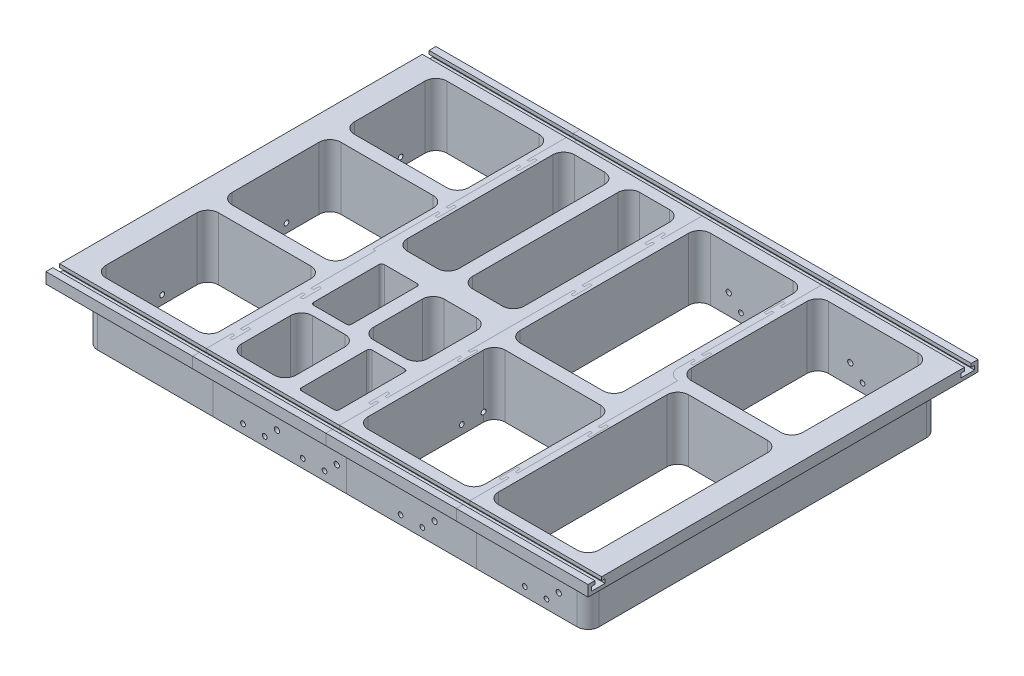
SolidWorks part; units mm, degrees
ref_plane "Front Plane" through (0, 0, 0) normal (0, 0, 1) x (1, 0, 0)
ref_plane "Top Plane" through (0, 0, 0) normal (0, 1, 0) x (1, 0, 0)
ref_plane "Right Plane" through (0, 0, 0) normal (1, 0, 0) x (0, 0, -1)
sketch "Sketch1" plane through (0, 0, 0) normal (0, 1, 0) x (1, 0, 0)
  line L1 (199.5, -143.5) -> (-199.5, -143.5)
  line L2 (199.5, -143.5) -> (199.5, 143.5)
  line L3 (199.5, 143.5) -> (-199.5, 143.5)
  line L4 (-199.5, -143.5) -> (-199.5, 143.5)
  line L5 (199.5, -143.5) -> (-199.5, 143.5) construction
  line L6 (199.5, 143.5) -> (-199.5, -143.5) construction
  point P0 (0, 0)
  dimension "D1" = 399
  dimension "D2" = 287
extrude "Boss-Extrude1" add sketch "Sketch1" along normal blind 53
sketch "Sketch3" plane through (0, 0, 0) normal (0, -1, 0) x (-1, 0, 0)
  line L23 (184.5, -128.5) -> (184.5, 128.5)
  line L24 (184.5, 128.5) -> (-184.5, 128.5)
  line L25 (-184.5, 128.5) -> (-184.5, -128.5)
  line L26 (-184.5, -128.5) -> (184.5, -128.5)
  line L27 (184.5, -128.5) -> (184.5, 128.5)
  line L28 (184.5, 128.5) -> (-184.5, 128.5)
  line L29 (-184.5, 128.5) -> (-184.5, -128.5)
  line L30 (-184.5, -128.5) -> (184.5, -128.5)
  dimension "D1" = 15
extrude "Cut-Extrude2" cut sketch "Sketch3" against normal blind 45 flip side to cut
sketch "Sketch2" plane through (0, 53, 0) normal (0, 1, 0) x (1, 0, 0)
  line L1 (-173.5, -125.5) -> (-105.5, -125.5)
  line L2 (-181.5, -117.5) -> (-181.5, -50.5)
  line L3 (-173.5, -42.5) -> (-105.5, -42.5)
  line L4 (-97.5, -117.5) -> (-97.5, -50.5)
  line L5 (-173.5, -32.5) -> (-105.5, -32.5)
  line L6 (-181.5, -24.5) -> (-181.5, 39.5)
  line L7 (-173.5, 47.5) -> (-105.5, 47.5)
  line L8 (-181.5, 125.5) -> (-181.5, -125.5)
  line L9 (-181.5, -125.5) -> (181.5, -125.5)
  line L10 (181.5, -125.5) -> (181.5, 125.5)
  line L11 (181.5, 125.5) -> (-181.5, 125.5)
  line L12 (-181.5, 125.5) -> (-181.5, -125.5) construction
  line L13 (-181.5, -125.5) -> (181.5, -125.5) construction
  line L14 (181.5, -125.5) -> (181.5, 125.5) construction
  line L15 (181.5, 125.5) -> (-181.5, 125.5) construction
  line L16 (-97.5, -24.5) -> (-97.5, 39.5)
  line L17 (-173.5, 125.5) -> (-105.5, 125.5)
  line L18 (-181.5, 117.5) -> (-181.5, 65.5)
  line L19 (-173.5, 57.5) -> (-105.5, 57.5)
  line L20 (-97.5, 117.5) -> (-97.5, 65.5)
  line L21 (173.5, -125.5) -> (115.5, -125.5)
  line L22 (181.5, -117.5) -> (181.5, 6.5)
  line L23 (173.5, 14.5) -> (115.5, 14.5)
  line L24 (107.5, -117.5) -> (107.5, 6.5)
  line L25 (173.5, 125.5) -> (107.5, 125.5)
  line L26 (181.5, 117.5) -> (181.5, 32.5)
  line L27 (173.5, 24.5) -> (107.5, 24.5)
  line L28 (99.5, 117.5) -> (99.5, 32.5)
  line L29 (81.5, 125.5) -> (20.5, 125.5)
  line L30 (89.5, 117.5) -> (89.5, -6.5)
  line L31 (81.5, -14.5) -> (20.5, -14.5)
  line L32 (12.5, 117.5) -> (12.5, -6.5)
  line L33 (-9.5, 125.5) -> (-31.5, 125.5)
  line L34 (-1.5, 117.5) -> (-1.5, 10.5)
  line L35 (-9.5, 2.5) -> (-31.5, 2.5)
  line L36 (-39.5, 117.5) -> (-39.5, 10.5)
  line L37 (-57.5, 125.5) -> (-79.5, 125.5)
  line L38 (-49.5, 117.5) -> (-49.5, 10.5)
  line L39 (-57.5, 2.5) -> (-79.5, 2.5)
  line L40 (-87.5, 117.5) -> (-87.5, 10.5)
  line L41 (-79.5, -14.5) -> (-55.5, -14.5)
  line L42 (-81.5, -16.5) -> (-81.5, -64.5)
  line L43 (-79.5, -66.5) -> (-55.5, -66.5)
  line L44 (-53.5, -16.5) -> (-53.5, -64.5)
  line L45 (-73.5, -125.5) -> (-49.5, -125.5)
  line L46 (-81.5, -117.5) -> (-81.5, -81.5)
  line L47 (-73.5, -73.5) -> (-49.5, -73.5)
  line L48 (-41.5, -117.5) -> (-41.5, -81.5)
  line L49 (-35.5, -14.5) -> (-11.5, -14.5)
  line L50 (-43.5, -22.5) -> (-43.5, -58.5)
  line L51 (-35.5, -66.5) -> (-11.5, -66.5)
  line L52 (-3.5, -22.5) -> (-3.5, -58.5)
  line L53 (-29.5, -73.5) -> (-5.5, -73.5)
  line L54 (-31.5, -75.5) -> (-31.5, -123.5)
  line L55 (-29.5, -125.5) -> (-5.5, -125.5)
  line L56 (-3.5, -75.5) -> (-3.5, -123.5)
  line L57 (89.5, -125.5) -> (19.5, -125.5)
  line L58 (97.5, -117.5) -> (97.5, -32.5)
  line L59 (89.5, -24.5) -> (19.5, -24.5)
  line L60 (11.5, -117.5) -> (11.5, -32.5)
  arc A0 (-79.5, 125.5) -> (-87.5, 117.5) centre (-79.5, 117.5) ccw
  arc A1 (-79.5, 2.5) -> (-87.5, 10.5) centre (-79.5, 10.5) cw
  arc A2 (-49.5, 10.5) -> (-57.5, 2.5) centre (-57.5, 10.5) cw
  arc A3 (-57.5, 125.5) -> (-49.5, 117.5) centre (-57.5, 117.5) cw
  arc A4 (-31.5, 125.5) -> (-39.5, 117.5) centre (-31.5, 117.5) ccw
  arc A5 (-31.5, 2.5) -> (-39.5, 10.5) centre (-31.5, 10.5) cw
  arc A6 (-1.5, 10.5) -> (-9.5, 2.5) centre (-9.5, 10.5) cw
  arc A7 (-9.5, 125.5) -> (-1.5, 117.5) centre (-9.5, 117.5) cw
  arc A8 (20.5, 125.5) -> (12.5, 117.5) centre (20.5, 117.5) ccw
  arc A9 (20.5, -14.5) -> (12.5, -6.5) centre (20.5, -6.5) cw
  arc A10 (89.5, -6.5) -> (81.5, -14.5) centre (81.5, -6.5) cw
  arc A11 (81.5, 125.5) -> (89.5, 117.5) centre (81.5, 117.5) cw
  arc A12 (107.5, 125.5) -> (99.5, 117.5) centre (107.5, 117.5) ccw
  arc A13 (173.5, 125.5) -> (181.5, 117.5) centre (173.5, 117.5) cw
  arc A14 (181.5, 32.5) -> (173.5, 24.5) centre (173.5, 32.5) cw
  arc A15 (107.5, 24.5) -> (99.5, 32.5) centre (107.5, 32.5) cw
  arc A16 (115.5, 14.5) -> (107.5, 6.5) centre (115.5, 6.5) ccw
  arc A17 (181.5, 6.5) -> (173.5, 14.5) centre (173.5, 6.5) ccw
  arc A18 (173.5, -125.5) -> (181.5, -117.5) centre (173.5, -117.5) ccw
  arc A19 (115.5, -125.5) -> (107.5, -117.5) centre (115.5, -117.5) cw
  arc A20 (89.5, -125.5) -> (97.5, -117.5) centre (89.5, -117.5) ccw
  arc A21 (97.5, -32.5) -> (89.5, -24.5) centre (89.5, -32.5) ccw
  arc A22 (19.5, -24.5) -> (11.5, -32.5) centre (19.5, -32.5) ccw
  arc A23 (19.5, -125.5) -> (11.5, -117.5) centre (19.5, -117.5) cw
  arc A28 (-43.5, -58.5) -> (-35.5, -66.5) centre (-35.5, -58.5) ccw
  arc A29 (-11.5, -66.5) -> (-3.5, -58.5) centre (-11.5, -58.5) ccw
  arc A30 (-11.5, -14.5) -> (-3.5, -22.5) centre (-11.5, -22.5) cw
  arc A31 (-35.5, -14.5) -> (-43.5, -22.5) centre (-35.5, -22.5) ccw
  arc A36 (-49.5, -73.5) -> (-41.5, -81.5) centre (-49.5, -81.5) cw
  arc A37 (-49.5, -125.5) -> (-41.5, -117.5) centre (-49.5, -117.5) ccw
  arc A38 (-73.5, -125.5) -> (-81.5, -117.5) centre (-73.5, -117.5) cw
  arc A39 (-81.5, -81.5) -> (-73.5, -73.5) centre (-73.5, -81.5) cw
  arc A40 (-105.5, -42.5) -> (-97.5, -50.5) centre (-105.5, -50.5) cw
  arc A41 (-105.5, -125.5) -> (-97.5, -117.5) centre (-105.5, -117.5) ccw
  arc A42 (-173.5, -125.5) -> (-181.5, -117.5) centre (-173.5, -117.5) cw
  arc A43 (-181.5, -50.5) -> (-173.5, -42.5) centre (-173.5, -50.5) cw
  arc A44 (-105.5, 47.5) -> (-97.5, 39.5) centre (-105.5, 39.5) cw
  arc A45 (-105.5, -32.5) -> (-97.5, -24.5) centre (-105.5, -24.5) ccw
  arc A46 (-173.5, -32.5) -> (-181.5, -24.5) centre (-173.5, -24.5) cw
  arc A47 (-181.5, 39.5) -> (-173.5, 47.5) centre (-173.5, 39.5) cw
  arc A48 (-105.5, 125.5) -> (-97.5, 117.5) centre (-105.5, 117.5) cw
  arc A49 (-105.5, 57.5) -> (-97.5, 65.5) centre (-105.5, 65.5) ccw
  arc A50 (-181.5, 65.5) -> (-173.5, 57.5) centre (-173.5, 65.5) ccw
  arc A51 (-173.5, 125.5) -> (-181.5, 117.5) centre (-173.5, 117.5) ccw
  arc A52 (-81.5, -16.5) -> (-79.5, -14.5) centre (-79.5, -16.5) cw
  arc A53 (-79.5, -66.5) -> (-81.5, -64.5) centre (-79.5, -64.5) cw
  arc A54 (-53.5, -64.5) -> (-55.5, -66.5) centre (-55.5, -64.5) cw
  arc A55 (-55.5, -14.5) -> (-53.5, -16.5) centre (-55.5, -16.5) cw
  arc A56 (-3.5, -75.5) -> (-5.5, -73.5) centre (-5.5, -75.5) ccw
  arc A57 (-5.5, -125.5) -> (-3.5, -123.5) centre (-5.5, -123.5) ccw
  arc A58 (-31.5, -123.5) -> (-29.5, -125.5) centre (-29.5, -123.5) ccw
  arc A59 (-31.5, -75.5) -> (-29.5, -73.5) centre (-29.5, -75.5) cw
  point P54 (-87.5, 125.5)
  point P57 (-87.5, 2.5)
  point P62 (-49.5, 125.5)
  point P65 (-39.5, 125.5)
  point P72 (-1.5, 125.5)
  point P75 (12.5, 125.5)
  point P82 (89.5, 125.5)
  point P85 (99.5, 125.5)
  point P91 (181.5, 24.5)
  point P103 (107.5, -125.5)
  point P106 (97.5, -125.5)
  point P109 (97.5, -24.5)
  point P114 (11.5, -125.5)
  point P119 (-3.5, -125.5)
  point P122 (-31.5, -125.5)
  point P127 (-43.5, -66.5)
  point P130 (-3.5, -66.5)
  point P139 (-81.5, -14.5)
  point P142 (-81.5, -66.5)
  point P149 (-41.5, -125.5)
  point P152 (-81.5, -125.5)
  point P155 (-81.5, -73.5)
  point P171 (-181.5, -32.5)
  point P174 (-181.5, 47.5)
  point P177 (-97.5, 125.5)
  point P182 (-181.5, 57.5)
  point P188 (-81.5, -14.5)
  point P191 (-81.5, -66.5)
  point P200 (-3.5, -125.5)
  point P203 (-31.5, -125.5)
  dimension "D31" = 8
  dimension "D32" = 8
  dimension "D33" = 8
  dimension "D34" = 2
  dimension "D35" = 2
  dimension "D2" = 74
  dimension "D3" = 82
  dimension "D4" = 101
  dimension "D5" = 10
  dimension "D6" = 86
  dimension "D7" = 10
  dimension "D8" = 15
  dimension "D9" = 28
  dimension "D10" = 40
  dimension "D11" = 52
  dimension "D12" = 52
  dimension "D13" = 77
  dimension "D14" = 38
  dimension "D15" = 38
  dimension "D16" = 84
  dimension "D17" = 68
  dimension "D18" = 80
  dimension "D19" = 10
  dimension "D20" = 10
  dimension "D21" = 7
  dimension "D22" = 10
  dimension "D23" = 101
  dimension "D24" = 10
  dimension "D25" = 10
  dimension "D26" = 123
  dimension "D27" = 10
  dimension "D28" = 10
  dimension "D29" = 40
  dimension "D30" = 10
  dimension "D1" = 18
extrude "Mini bin cuts" cut sketch "Sketch2" against normal blind 46
fillet "Fillet1" radius 8 4 edges at (-184.5, 22.5, -128.5) (184.5, 22.5, -128.5) (184.5, 22.5, 128.5) (-184.5, 22.5, 128.5)
sketch "Sketch6" plane through (-184.5, 0, 0) normal (-1, 0, 0) x (0, 0, 1)
  line L0 (128.5, 45) -> (128.5, 0) construction
  line L1 (-128.5, 0) -> (128.5, 0)
  line L2 (-128.5, 0) -> (-128.5, 7)
  line L3 (-128.5, 7) -> (128.5, 7)
  line L4 (128.5, 0) -> (128.5, 7)
  dimension "D1" = 7
extrude "Cut-Extrude5" cut sketch "Sketch6" against normal through all
sketch "Sketch7" plane through (-184.5, 0, 0) normal (-1, 0, 0) x (0, 0, 1)
  line L0 (-120.5, 13.5) -> (120.5, 13.5) construction
  line L1 (-120.5, 45) -> (-120.5, 7) construction
  line L2 (120.5, 7) -> (120.5, 45) construction
  line L3 (120.5, 7) -> (-120.5, 7) construction
  line L4 (-91.5, 13.5) -> (-91.5, 45) construction
  line L5 (120.5, 45) -> (-120.5, 45) construction
  line L6 (-7.5, 13.5) -> (-7.5, 45) construction
  line L7 (84, 13.5) -> (84, 45) construction
  circle A0 centre (-99.5, 13.5) radius 1.75
  circle A1 centre (-83.5, 13.5) radius 1.75
  circle A2 centre (-15.5, 13.5) radius 1.75
  circle A3 centre (76, 13.5) radius 1.75
  circle A4 centre (0.5, 13.5) radius 1.75
  circle A5 centre (92, 13.5) radius 1.75
  circle A6 centre (-74.5, 21.963) radius 1.95
  circle A7 centre (101, 21.963) radius 1.95
  circle A8 centre (9.5, 21.963) radius 1.95
  dimension "D2" = 36.5
  dimension "D5" = 3.5
  dimension "D7" = 3.5
  dimension "D9" = 3.5
  dimension "D11" = 3.9
  dimension "D12" = 3.9
  dimension "D13" = 3.9
  dimension "D1" = 6.5
  dimension "D3" = 29
  dimension "D4" = 113
  dimension "D6" = 8
  dimension "D8" = 8
  dimension "D10" = 8
  dimension "D14" = 17
  dimension "D15" = 17
  dimension "D16" = 17
  dimension "D17" = 8.463
  dimension "D18" = 8.463
  dimension "D19" = 8.463
extrude "Holes Lids 1,2,3" cut sketch "Sketch7" against normal up to surface (3 mm away) up to face at (-181.5, 30, 84)
sketch "Sketch8" plane through (0, 0, 128.5) normal (0, 0, 1) x (1, 0, 0)
  line L0 (-176.5, 13.5) -> (176.5, 13.5) construction
  line L1 (-176.5, 45) -> (-176.5, 7) construction
  line L2 (176.5, 7) -> (176.5, 45) construction
  line L5 (-61.5, 45) -> (-61.5, 7) construction
  line L6 (176.5, 45) -> (-176.5, 45) construction
  line L7 (176.5, 7) -> (-176.5, 7) construction
  line L8 (-17.5, 45) -> (-17.5, 7) construction
  line L11 (145.896, 45) -> (145.896, 7) construction
  line L12 (54.5, 45) -> (54.5, 7) construction
  circle A0 centre (-69.5, 13.5) radius 1.75
  circle A1 centre (-25.5, 13.5) radius 1.75
  circle A2 centre (46.5, 13.5) radius 1.75
  circle A3 centre (137.896, 13.5) radius 1.75
  circle A4 centre (153.896, 13.5) radius 1.75
  circle A5 centre (62.5, 13.5) radius 1.75
  circle A6 centre (-9.5, 13.5) radius 1.75
  circle A7 centre (-53.5, 13.5) radius 1.75
  circle A8 centre (-44.5, 21.96) radius 1.95
  circle A9 centre (-0.5, 21.96) radius 1.95
  circle A10 centre (71.5, 21.96) radius 1.95
  circle A11 centre (162.896, 21.96) radius 1.95
  dimension "D5" = 3.5
  dimension "D6" = 3.5
  dimension "D7" = 3.5
  dimension "D8" = 3.5
  dimension "D14" = 3.9
  dimension "D16" = 8.46
  dimension "D17" = 17
  dimension "D18" = 8.46
  dimension "D19" = 17
  dimension "D20" = 8.46
  dimension "D22" = 8.46
  dimension "D1" = 115
  dimension "D2" = 159
  dimension "D3" = 6.5
  dimension "D4" = 122
  dimension "D9" = 8
  dimension "D10" = 8
  dimension "D11" = 8
  dimension "D12" = 8
  dimension "D13" = 30.604
  dimension "D15" = 17
  dimension "D21" = 17
extrude "Holes Lids 8,9,12,13" cut sketch "Sketch8" against normal up to surface (3 mm away) up to face at (54.5, 30, 125.5)
sketch "Sketch9" plane through (0, 0, -128.5) normal (0, 0, -1) x (-1, 0, 0)
  line L0 (-176.5, 13.5) -> (176.5, 13.5) construction
  line L1 (-176.5, 45) -> (-176.5, 7) construction
  line L2 (176.5, 7) -> (176.5, 45) construction
  line L3 (-140.5, 45) -> (-140.5, 7) construction
  line L4 (176.5, 45) -> (-176.5, 45) construction
  line L5 (-176.5, 7) -> (176.5, 7) construction
  line L7 (20.5, 45) -> (20.5, 7) construction
  line L8 (199.5, 45) -> (-199.5, 45) construction
  line L9 (68.5, 45) -> (68.5, 7) construction
  line L10 (-51, 45) -> (-51, 7) construction
  circle A0 centre (-148.5, 13.5) radius 1.75
  circle A1 centre (-59, 13.5) radius 1.75
  circle A2 centre (12.5, 13.5) radius 1.75
  circle A3 centre (60.5, 13.5) radius 1.75
  circle A4 centre (-132.5, 13.5) radius 1.75
  circle A5 centre (-43, 13.5) radius 1.75
  circle A6 centre (28.5, 13.5) radius 1.75
  circle A7 centre (76.5, 13.5) radius 1.75
  circle A8 centre (-123.5, 21.96) radius 1.95
  circle A9 centre (-34, 21.96) radius 1.95
  circle A10 centre (37.5, 21.96) radius 1.95
  circle A11 centre (85.5, 21.96) radius 1.95
  dimension "D6" = 3.5
  dimension "D10" = 8
  dimension "D11" = 3.5
  dimension "D12" = 3.5
  dimension "D13" = 3.5
  dimension "D14" = 3.9
  dimension "D15" = 3.9
  dimension "D16" = 3.9
  dimension "D17" = 17
  dimension "D19" = 17
  dimension "D20" = 8.46
  dimension "D21" = 8.46
  dimension "D22" = 8.46
  dimension "D23" = 8.46
  dimension "D24" = 3.9
  dimension "D25" = 17
  dimension "D1" = 6.5
  dimension "D2" = 36
  dimension "D3" = 125.5
  dimension "D4" = 197
  dimension "D5" = 245
  dimension "D7" = 8
  dimension "D8" = 8
  dimension "D9" = 8
  dimension "D18" = 17
extrude "Holes Lids 4,5,10,11" cut sketch "Sketch9" against normal up to surface (3 mm away) up to face at (51, 30, -125.5)
sketch "Sketch11" plane through (-3.5, 0, 0) normal (-1, 0, 0) x (0, 0, 1)
  line L0 (22.5, 13.5) -> (58.5, 13.5) construction
  line L1 (22.5, 7) -> (22.5, 53) construction
  line L2 (58.5, 7) -> (58.5, 53) construction
  line L3 (40.5, 7) -> (40.5, 53) construction
  line L4 (58.5, 7) -> (22.5, 7) construction
  line L5 (22.5, 53) -> (58.5, 53) construction
  circle A0 centre (32.5, 13.5) radius 1.75
  circle A1 centre (48.5, 13.5) radius 1.75
  dimension "D2" = 3.5
  dimension "D1" = 6.5
  dimension "D3" = 8
extrude "Hole Lid 7" cut sketch "Sketch11" against normal up to next
sketch "Sketch12" plane through (-81.5, 0, 0) normal (1, 0, 0) x (0, 0, -1)
  line L0 (-64.5, 13.5) -> (-16.5, 13.5) construction
  line L1 (-64.5, 7) -> (-64.5, 53) construction
  line L2 (-16.5, 7) -> (-16.5, 53) construction
  line L3 (-40.5, 7) -> (-40.5, 53) construction
  line L5 (-16.5, 7) -> (-64.5, 7) construction
  line L6 (-16.5, 53) -> (-64.5, 53) construction
  circle A0 centre (-48.5, 13.5) radius 1.75
  circle A1 centre (-32.5, 13.5) radius 1.75
  dimension "D2" = 3.5
  dimension "D1" = 6.5
  dimension "D3" = 8
extrude "Hole Lid 6" cut sketch "Sketch12" against normal blind 15
sketch "Split Lines" plane through (0, 53, 0) normal (0, 1, 0) x (1, 0, 0)
  line L1 (-97.5, 117.5) -> (-97.5, 65.5) construction
  line L3 (-79.5, -14.5) -> (-55.5, -14.5) construction
  line L4 (173.5, 14.5) -> (115.5, 14.5) construction
  line L5 (-93.5, 143.5) -> (-93.5, 104.5)
  line L6 (199.5, 143.5) -> (-199.5, 143.5) construction
  line L7 (-199.5, -143.5) -> (199.5, -143.5) construction
  line L8 (-90.25, -114.5) -> (-91.5, -114.5)
  line L9 (-89.5, -117.75) -> (-89.5, -115.25)
  line L10 (-88.25, -118.5) -> (-88.75, -118.5)
  line L11 (-87.5, -105.25) -> (-87.5, -117.75)
  line L12 (-88.75, -104.5) -> (-88.25, -104.5)
  line L13 (-89.5, -107.75) -> (-89.5, -105.25)
  line L14 (-93.5, 45) -> (-92.5, 45)
  line L15 (-91.75, 45.75) -> (-91.75, 48.25)
  line L16 (-91, 49) -> (-90.5, 49)
  line L17 (-89.75, 48.25) -> (-89.75, 35.75)
  line L18 (-90.5, 35) -> (-91, 35)
  line L19 (-91.75, 35.75) -> (-91.75, 38.25)
  line L20 (-92.5, 39) -> (-93.5, 39)
  line L21 (-93.5, 39) -> (-93.5, -8)
  line L22 (-91.5, -143.5) -> (-91.5, -114.5)
  line L23 (-81.5, -117.5) -> (-81.5, -81.5) construction
  line L24 (-81.5, -16.5) -> (-81.5, -64.5) construction
  line L25 (89.5, -24.5) -> (19.5, -24.5) construction
  line L37 (-93.5, 98.5) -> (-93.5, 45)
  line L39 (6.5, 143.5) -> (6.5, 104.5)
  line L40 (-1.5, 117.5) -> (-1.5, 10.5) construction
  line L41 (6.5, 104.5) -> (5.5, 104.5)
  line L42 (4.75, 105.25) -> (4.75, 107.75)
  line L43 (4, 108.5) -> (3.5, 108.5)
  line L44 (2.75, 107.75) -> (2.75, 95.25)
  line L45 (3.5, 94.5) -> (4, 94.5)
  line L46 (4.75, 95.25) -> (4.75, 97.75)
  line L47 (5.5, 98.5) -> (6.5, 98.5)
  line L48 (7.5, -39) -> (6.5, -39)
  line L49 (8.25, -35.75) -> (8.25, -38.25)
  line L50 (6.5, 45) -> (8.25, 45)
  line L51 (8.25, 45) -> (8.25, 48.25)
  line L52 (9, 49) -> (9.5, 49)
  line L53 (10.25, 48.25) -> (10.25, 35.75)
  line L54 (9.5, 35) -> (9, 35)
  line L55 (8.25, 35.75) -> (8.25, 38.25)
  line L56 (7.5, 39) -> (7.25, 39)
  line L57 (9.5, -35) -> (9, -35)
  line L58 (10.25, -48.25) -> (10.25, -35.75)
  line L59 (9, -49) -> (9.5, -49)
  line L60 (8.25, -45.75) -> (8.25, -48.25)
  line L61 (6.5, -45) -> (7.5, -45)
  line L62 (5.5, -98.5) -> (6.5, -98.5)
  line L63 (4.75, -95.25) -> (4.75, -97.75)
  line L64 (3.5, -94.5) -> (4, -94.5)
  line L65 (2.75, -107.75) -> (2.75, -95.25)
  line L66 (4, -108.5) -> (3.5, -108.5)
  line L67 (4.75, -105.25) -> (4.75, -107.75)
  line L68 (6.5, -104.5) -> (5.5, -104.5)
  line L69 (94.5, 143.5) -> (94.5, 104.5)
  line L71 (102.5, 19.5) -> (102.5, -39)
  line L72 (89.5, 117.5) -> (89.5, -6.5) construction
  line L73 (107.5, -117.5) -> (107.5, 6.5) construction
  line L74 (94.5, 104.5) -> (93.5, 104.5)
  line L75 (92.75, 105.25) -> (92.75, 107.75)
  line L76 (92, 108.5) -> (91.5, 108.5)
  line L77 (90.75, 107.75) -> (90.75, 95.25)
  line L78 (91.5, 94.5) -> (92, 94.5)
  line L79 (92.75, 95.25) -> (92.75, 97.75)
  line L80 (93.5, 98.5) -> (94.5, 98.5)
  line L81 (94.5, 45) -> (95.5, 45)
  line L82 (96.25, 45.75) -> (96.25, 48.25)
  line L83 (97, 49) -> (97.5, 49)
  line L84 (98.25, 48.25) -> (98.25, 35.75)
  line L85 (97.5, 35) -> (97, 35)
  line L86 (96.25, 35.75) -> (96.25, 38.25)
  line L87 (95.5, 39) -> (94.5, 39)
  line L88 (102.5, -39) -> (103.5, -39)
  line L89 (104.25, -38.25) -> (104.25, -35.75)
  line L90 (105, -35) -> (105.5, -35)
  line L91 (106.25, -35.75) -> (106.25, -48.25)
  line L92 (105.5, -49) -> (105, -49)
  line L93 (104.25, -48.25) -> (104.25, -45.75)
  line L94 (103.5, -45) -> (102.5, -45)
  line L95 (102.5, -98.5) -> (101.5, -98.5)
  line L96 (100.75, -97.75) -> (100.75, -95.25)
  line L97 (100, -94.5) -> (99.5, -94.5)
  line L98 (98.75, -95.25) -> (98.75, -107.75)
  line L99 (99.5, -108.5) -> (100, -108.5)
  line L100 (100.75, -107.75) -> (100.75, -105.25)
  line L101 (101.5, -104.5) -> (102.5, -104.5)
  line L102 (6.5, 98.5) -> (6.5, 45)
  line L103 (6.5, 38.25) -> (6.5, -39)
  line L104 (6.5, -45) -> (6.5, -98.5)
  line L105 (6.5, -104.5) -> (6.5, -143.5)
  line L106 (102.5, -104.5) -> (102.5, -143.5)
  line L107 (102.5, -45) -> (102.5, -98.5)
  line L108 (94.5, 39) -> (94.5, 27.5)
  line L109 (94.5, 98.5) -> (94.5, 45)
  line L111 (-91.5, -56.5) -> (-90.25, -56.5)
  line L113 (-89.5, -55.75) -> (-89.5, -53.25)
  line L115 (-88.75, -52.5) -> (-88.25, -52.5)
  line L118 (-199.5, 143.5) -> (-199.5, -143.5) construction
  line L119 (-87.5, -53.25) -> (-87.5, -65.75)
  line L120 (-88.25, -66.5) -> (-88.75, -66.5)
  line L121 (-89.5, -65.75) -> (-89.5, -63.25)
  line L122 (-90.25, -62.5) -> (-91.5, -62.5)
  line L126 (-91.5, -108.5) -> (-91.5, -62.5)
  line L131 (-91.5, -56.5) -> (-91.5, -9)
  line L133 (199.5, -140.5) -> (-199.5, -140.5) construction
  line L141 (-92.5, 98.5) -> (-93.5, 98.5)
  line L142 (-91.75, 95.25) -> (-91.75, 97.75)
  line L143 (-90.5, 94.5) -> (-91, 94.5)
  line L144 (-89.75, 107.75) -> (-89.75, 95.25)
  line L145 (-91, 108.5) -> (-90.5, 108.5)
  line L147 (81.5, -14.5) -> (20.5, -14.5) construction
  line L175 (-91.75, 105.25) -> (-91.75, 107.75)
  line L182 (-92.5, -9) -> (-91.5, -9)
  line L190 (-93.5, 104.5) -> (-92.5, 104.5)
  line L191 (-91.5, -108.5) -> (-90.25, -108.5)
  line L198 (-73.5, -125.5) -> (-49.5, -125.5) construction
  arc A0 (102.5, 19.5) -> (94.5, 27.5) centre (102.5, 27.5) cw
  arc A1 (-92.5, -9) -> (-93.5, -8) centre (-92.5, -8) cw
  arc A2 (4.75, -105.25) -> (5.5, -104.5) centre (5.5, -105.25) cw
  arc A14 (-89.5, -107.75) -> (-90.25, -108.5) centre (-90.25, -107.75) cw
  arc A15 (-90.25, -114.5) -> (-89.5, -115.25) centre (-90.25, -115.25) cw
  arc A16 (-88.75, -118.5) -> (-89.5, -117.75) centre (-88.75, -117.75) cw
  arc A17 (-88.25, -118.5) -> (-87.5, -117.75) centre (-88.25, -117.75) ccw
  arc A18 (-87.5, -105.25) -> (-88.25, -104.5) centre (-88.25, -105.25) ccw
  arc A19 (-89.5, -105.25) -> (-88.75, -104.5) centre (-88.75, -105.25) cw
  arc A20 (-88.25, -66.5) -> (-87.5, -65.75) centre (-88.25, -65.75) ccw
  arc A21 (-88.75, -66.5) -> (-89.5, -65.75) centre (-88.75, -65.75) cw
  arc A22 (-89.5, -63.25) -> (-90.25, -62.5) centre (-90.25, -63.25) ccw
  arc A23 (-89.5, -55.75) -> (-90.25, -56.5) centre (-90.25, -55.75) cw
  arc A24 (-89.5, -53.25) -> (-88.75, -52.5) centre (-88.75, -53.25) cw
  arc A25 (-88.25, -52.5) -> (-87.5, -53.25) centre (-88.25, -53.25) cw
  arc A32 (-90.5, 49) -> (-89.75, 48.25) centre (-90.5, 48.25) cw
  arc A33 (-91.75, 48.25) -> (-91, 49) centre (-91, 48.25) cw
  arc A34 (-92.5, 45) -> (-91.75, 45.75) centre (-92.5, 45.75) ccw
  arc A35 (-89.75, 35.75) -> (-90.5, 35) centre (-90.5, 35.75) cw
  arc A36 (-91, 35) -> (-91.75, 35.75) centre (-91, 35.75) cw
  arc A37 (-91.75, 38.25) -> (-92.5, 39) centre (-92.5, 38.25) ccw
  arc A50 (7.25, 39) -> (6.5, 38.25) centre (7.25, 38.25) ccw
  arc A51 (8.25, 38.25) -> (7.5, 39) centre (7.5, 38.25) ccw
  arc A52 (9, 35) -> (8.25, 35.75) centre (9, 35.75) cw
  arc A53 (10.25, 35.75) -> (9.5, 35) centre (9.5, 35.75) cw
  arc A54 (9.5, 49) -> (10.25, 48.25) centre (9.5, 48.25) cw
  arc A55 (8.25, 48.25) -> (9, 49) centre (9, 48.25) cw
  arc A56 (2.75, 95.25) -> (3.5, 94.5) centre (3.5, 95.25) ccw
  arc A57 (4, 94.5) -> (4.75, 95.25) centre (4, 95.25) ccw
  arc A58 (4.75, 97.75) -> (5.5, 98.5) centre (5.5, 97.75) cw
  arc A59 (5.5, 104.5) -> (4.75, 105.25) centre (5.5, 105.25) cw
  arc A60 (3.5, 108.5) -> (2.75, 107.75) centre (3.5, 107.75) ccw
  arc A61 (4.75, 107.75) -> (4, 108.5) centre (4, 107.75) ccw
  arc A62 (4, -108.5) -> (4.75, -107.75) centre (4, -107.75) ccw
  arc A63 (2.75, -107.75) -> (3.5, -108.5) centre (3.5, -107.75) ccw
  arc A64 (3.5, -94.5) -> (2.75, -95.25) centre (3.5, -95.25) ccw
  arc A65 (4.75, -95.25) -> (4, -94.5) centre (4, -95.25) ccw
  arc A66 (5.5, -98.5) -> (4.75, -97.75) centre (5.5, -97.75) cw
  arc A67 (8.25, -45.75) -> (7.5, -45) centre (7.5, -45.75) ccw
  arc A68 (9, -49) -> (8.25, -48.25) centre (9, -48.25) cw
  arc A69 (10.25, -48.25) -> (9.5, -49) centre (9.5, -48.25) cw
  arc A70 (9.5, -35) -> (10.25, -35.75) centre (9.5, -35.75) cw
  arc A71 (8.25, -35.75) -> (9, -35) centre (9, -35.75) cw
  arc A72 (7.5, -39) -> (8.25, -38.25) centre (7.5, -38.25) ccw
  arc A73 (104.25, -45.75) -> (103.5, -45) centre (103.5, -45.75) ccw
  arc A74 (105, -49) -> (104.25, -48.25) centre (105, -48.25) cw
  arc A75 (106.25, -48.25) -> (105.5, -49) centre (105.5, -48.25) cw
  arc A76 (105.5, -35) -> (106.25, -35.75) centre (105.5, -35.75) cw
  arc A77 (104.25, -35.75) -> (105, -35) centre (105, -35.75) cw
  arc A78 (103.5, -39) -> (104.25, -38.25) centre (103.5, -38.25) ccw
  arc A79 (100.75, -105.25) -> (101.5, -104.5) centre (101.5, -105.25) cw
  arc A80 (100, -108.5) -> (100.75, -107.75) centre (100, -107.75) ccw
  arc A81 (98.75, -107.75) -> (99.5, -108.5) centre (99.5, -107.75) ccw
  arc A82 (99.5, -94.5) -> (98.75, -95.25) centre (99.5, -95.25) ccw
  arc A83 (100.75, -95.25) -> (100, -94.5) centre (100, -95.25) ccw
  arc A84 (101.5, -98.5) -> (100.75, -97.75) centre (101.5, -97.75) cw
  arc A108 (92.75, 97.75) -> (93.5, 98.5) centre (93.5, 97.75) cw
  arc A109 (92, 94.5) -> (92.75, 95.25) centre (92, 95.25) ccw
  arc A110 (90.75, 95.25) -> (91.5, 94.5) centre (91.5, 95.25) ccw
  arc A111 (91.5, 108.5) -> (90.75, 107.75) centre (91.5, 107.75) ccw
  arc A112 (92.75, 107.75) -> (92, 108.5) centre (92, 107.75) ccw
  arc A113 (93.5, 104.5) -> (92.75, 105.25) centre (93.5, 105.25) cw
  arc A114 (96.25, 38.25) -> (95.5, 39) centre (95.5, 38.25) ccw
  arc A115 (97, 35) -> (96.25, 35.75) centre (97, 35.75) cw
  arc A116 (98.25, 35.75) -> (97.5, 35) centre (97.5, 35.75) cw
  arc A117 (97.5, 49) -> (98.25, 48.25) centre (97.5, 48.25) cw
  arc A118 (95.5, 45) -> (96.25, 45.75) centre (95.5, 45.75) ccw
  arc A119 (96.25, 48.25) -> (97, 49) centre (97, 48.25) cw
  arc A120 (-91.75, 97.75) -> (-92.5, 98.5) centre (-92.5, 97.75) ccw
  arc A121 (-91, 94.5) -> (-91.75, 95.25) centre (-91, 95.25) cw
  arc A122 (-89.75, 95.25) -> (-90.5, 94.5) centre (-90.5, 95.25) cw
  arc A123 (-90.5, 108.5) -> (-89.75, 107.75) centre (-90.5, 107.75) cw
  arc A124 (-91.75, 107.75) -> (-91, 108.5) centre (-91, 107.75) cw
  arc A125 (-92.5, 104.5) -> (-91.75, 105.25) centre (-92.5, 105.25) ccw
  point P0 (-89.75, 42)
  point P2 (-224.5011, 0)
  point P3 (0, 0)
  point P17 (-89.75, 101.5)
  point P19 (6.5, 143.5)
  point P20 (94.5, 144.2544)
  point P21 (10.25, 42)
  point P34 (106.25, -42)
  point P37 (98.25, 42)
  point P38 (10.25, -42)
  point P82 (2.75, -101.5)
  point P91 (0, 0)
  point P92 (0, 0)
  point P93 (0, 0)
  point P138 (-87.5, -59.5)
  point P141 (0, 0)
  point P144 (-93.5, 157.3635)
  point P145 (-93.5, 167.5)
  point P148 (0, 0)
  point P149 (6.5, 155.6454)
  point P150 (6.5, 167.5)
  point P151 (-87.5, -111.5)
  point P153 (-91.5, -143.5)
  point P155 (6.5, -143.5)
  point P156 (0, 0)
  point P157 (94.5, 157.7999)
  point P158 (94.5, 167.5)
  point P231 (93.5, 130.3702)
  point P232 (5.5, 130.3702)
  point P265 (0, 0)
  point P266 (-91.5, -157.0413)
  point P267 (-91.5, -167.5)
  point P268 (0, 0)
  point P269 (6.5, -155.2132)
  point P270 (6.5, -167.5)
  point P271 (0, 0)
  point P272 (102.5, -159.2429)
  point P273 (102.5, -167.5)
  point P279 (-89.5, -66.5)
  point P283 (-89.5, -62.5)
  point P287 (-89.5, -56.5)
  point P292 (-89.5, -52.5)
  point P296 (-87.5, -52.5)
  point P297 (0, 0)
  point P298 (-193.427, -36)
  point P299 (-199.5, -36)
  point P300 (0, 0)
  point P301 (191.7613, 19.5)
  point P302 (199.5, 19.5)
  point P303 (0, 0)
  point P304 (0, 0)
  point P305 (0, 0)
  point P306 (-92.5, 130.3702)
  point P307 (123.2907, 180.4412)
  point P308 (0, 0)
  point P309 (-91.5, -133.1657)
  point P310 (0, 0)
  point P314 (-89.75, 49)
  point P317 (-91.75, 49)
  point P320 (-91.75, 45)
  point P323 (-89.75, 35)
  point P326 (-91.75, 35)
  point P329 (6.5, -131.5401)
  point P330 (0, 0)
  point P331 (101.5, -129.4308)
  point P332 (102.5, -143.5)
  point P333 (-93.5, 143.5)
  point P334 (94.5, 140.148)
  point P335 (94.5, 143.5)
  point P336 (0, 0)
  point P337 (0, 0)
  point P367 (6.5, 39)
  point P370 (8.25, 39)
  point P373 (8.25, 35)
  point P376 (10.25, 35)
  point P379 (10.25, 49)
  point P382 (8.25, 49)
  point P385 (2.75, 94.5)
  point P388 (4.75, 94.5)
  point P391 (4.75, 98.5)
  point P394 (4.75, 104.5)
  point P397 (2.75, 108.5)
  point P400 (4.75, 108.5)
  point P403 (4.75, -108.5)
  point P409 (2.75, -94.5)
  point P412 (4.75, -94.5)
  point P415 (4.75, -98.5)
  point P418 (8.25, -45)
  point P421 (8.25, -49)
  point P424 (10.25, -49)
  point P427 (10.25, -35)
  point P430 (8.25, -35)
  point P433 (8.25, -39)
  point P440 (106.25, -49)
  point P443 (106.25, -35)
  point P446 (104.25, -35)
  point P449 (104.25, -39)
  point P452 (100.75, -104.5)
  point P455 (100.75, -108.5)
  point P458 (98.75, -108.5)
  point P461 (98.75, -94.5)
  point P464 (100.75, -94.5)
  point P467 (100.75, -98.5)
  point P543 (90.75, 94.5)
  point P546 (90.75, 108.5)
  point P549 (92.75, 108.5)
  point P552 (92.75, 104.5)
  point P555 (96.25, 39)
  point P558 (96.25, 35)
  point P561 (98.25, 35)
  point P564 (98.25, 49)
  point P567 (96.25, 45)
  point P617 (-91.75, 98.5)
  point P618 (-89.75, 94.5)
  point P619 (-89.75, 108.5)
  point P621 (-91.75, 108.5)
  point P622 (-91.75, 104.5)
  dimension "D30" = 8
  dimension "D31" = 10
  dimension "D64" = 2
  dimension "D65" = 0.75
  dimension "D66" = 14
  dimension "D68" = 1.75
  dimension "D60" = 22.5
  dimension "D61" = 6
  dimension "D59" = 1
  dimension "D67" = 0.75
  dimension "D74" = 0.75
  dimension "D87" = 0.75
  dimension "D89" = 14
  dimension "D90" = 0.75
  dimension "D92" = 0.75
  dimension "D94" = 2.5
  dimension "D96" = 2
  dimension "D97" = 1.75
  dimension "D98" = 2
  dimension "D102" = 0.75
  dimension "D78" = 4
  dimension "D77" = 0.75
  dimension "D84" = 0.75
  dimension "D14" = 51
  dimension "D113" = 3
  dimension "D1" = 4
  dimension "D8" = 1.75
  dimension "D9" = 14
  dimension "D10" = 2
  dimension "D11" = 6
  dimension "D12" = 2
  dimension "D13" = 4
  dimension "D15" = 8
  dimension "D16" = 14
  dimension "D17" = 2
  dimension "D18" = 1.75
  dimension "D19" = 6
  dimension "D20" = 4
  dimension "D21" = 5.5
  dimension "D22" = 14
  dimension "D23" = 6
  dimension "D24" = 2
  dimension "D25" = 1.75
  dimension "D26" = 4
  dimension "D27" = 35
  dimension "D28" = 5
  dimension "D29" = 5
  dimension "D32" = 14
  dimension "D33" = 6
  dimension "D34" = 2
  dimension "D35" = 1.75
  dimension "D36" = 2
  dimension "D37" = 4
  dimension "D38" = 35
  dimension "D39" = 14
  dimension "D40" = 6
  dimension "D41" = 2
  dimension "D42" = 1.75
  dimension "D43" = 4
  dimension "D44" = 56.5
  dimension "D45" = 14
  dimension "D46" = 6
  dimension "D47" = 2
  dimension "D48" = 1.75
  dimension "D49" = 4
  dimension "D50" = 1.75
  dimension "D51" = 17.5
  dimension "D52" = 14
  dimension "D53" = 6
  dimension "D54" = 2
  dimension "D55" = 1.75
  dimension "D56" = 4
  dimension "D57" = 35
  dimension "D58" = 5
  dimension "D62" = 12.5
  dimension "D63" = 56.5
  dimension "D69" = 1.75
  dimension "D71" = 3.75
  dimension "D72" = 4
  dimension "D73" = 4
  dimension "D75" = 2
  dimension "D76" = 6
  dimension "D79" = 32
  dimension "D80" = 4
  dimension "D81" = 6
  dimension "D82" = 2
  dimension "D83" = 2
  dimension "D85" = 4
  dimension "D86" = 66
  dimension "D91" = 6
  dimension "D93" = 2.5
  dimension "D95" = 2
  dimension "D99" = 6
  dimension "D100" = 14
  dimension "D101" = 42
  dimension "D103" = 7
  dimension "D104" = 42
  dimension "D112" = 3.75
sketch "Sketch13" plane through (0, 7, 0) normal (0, -1, 0) x (1, 0, 0)
  line L0 (-81.5, 16.5) -> (-81.5, 64.5) construction
  line L1 (-173.5, 42.5) -> (-105.5, 42.5) construction
  line L2 (-91.5, 26.435) -> (-81.5, 26.435) construction
  line L3 (-91.5, 143.5) -> (-91.5, 114.5) construction
  line L4 (81.5, 14.5) -> (20.5, 14.5) construction
  line L5 (11.5, 37.905) -> (-3.5, 37.905) construction
  line L6 (11.5, 117.5) -> (11.5, 32.5) construction
  line L7 (-3.5, 22.5) -> (-3.5, 58.5) construction
  circle A0 centre (-88.5, 46.5) radius 1.95
  circle A1 centre (-88.5, 6.37) radius 1.95
  circle A2 centre (3.5, 17.84) radius 1.95
  circle A3 centre (3.5, 57.97) radius 1.95
  dimension "D1" = 3.9
  dimension "D3" = 4
  dimension "D5" = 3.9
  dimension "D8" = 7
  dimension "D2" = 7
  dimension "D4" = 20.065
  dimension "D6" = 3.34
  dimension "D7" = 20.065
extrude "Servo brackets 6,7," cut sketch "Sketch13" against normal blind 15
split "Split2" trim tools "Split Lines" bodies to split 145 resulting bodies 150 151 152 153
sketch "Sketch14" plane through (-199.5, 0, 0) normal (-1, 0, 0) x (0, 0, 1)
  line L0 (133.5, 53) -> (133.5, 50.5)
  line L1 (104.5, 53) -> (143.5, 53) construction
  line L2 (133.5, 50.5) -> (131, 50.5)
  line L3 (131, 50.5) -> (131, 47.5)
  line L4 (131, 47.5) -> (141, 47.5)
  line L5 (141, 47.5) -> (141, 50.5)
  line L6 (141, 50.5) -> (138.5, 50.5)
  line L7 (138.5, 50.5) -> (138.5, 53)
  line L8 (138.5, 53) -> (133.5, 53)
  line L9 (143.5, 53) -> (143.5, 45) construction
  line L10 (0, 0) -> (0, 45) construction
  line L11 (143.5, 45) -> (-143.5, 45) construction
  line L12 (-138.5, 53) -> (-133.5, 53)
  line L13 (-138.5, 50.5) -> (-138.5, 53)
  line L14 (-141, 50.5) -> (-138.5, 50.5)
  line L15 (-141, 47.5) -> (-141, 50.5)
  line L16 (-131, 47.5) -> (-141, 47.5)
  line L17 (-131, 50.5) -> (-131, 47.5)
  line L18 (-133.5, 50.5) -> (-131, 50.5)
  line L19 (-133.5, 53) -> (-133.5, 50.5)
  point P7 (136, 47.5)
  dimension "D1" = 10
  dimension "D2" = 5
  dimension "D3" = 3
  dimension "D4" = 2.5
  dimension "D5" = 2.5
  dimension "D6" = 7.5
extrude "Structural Cuts" cut sketch "Sketch14" against normal through all
